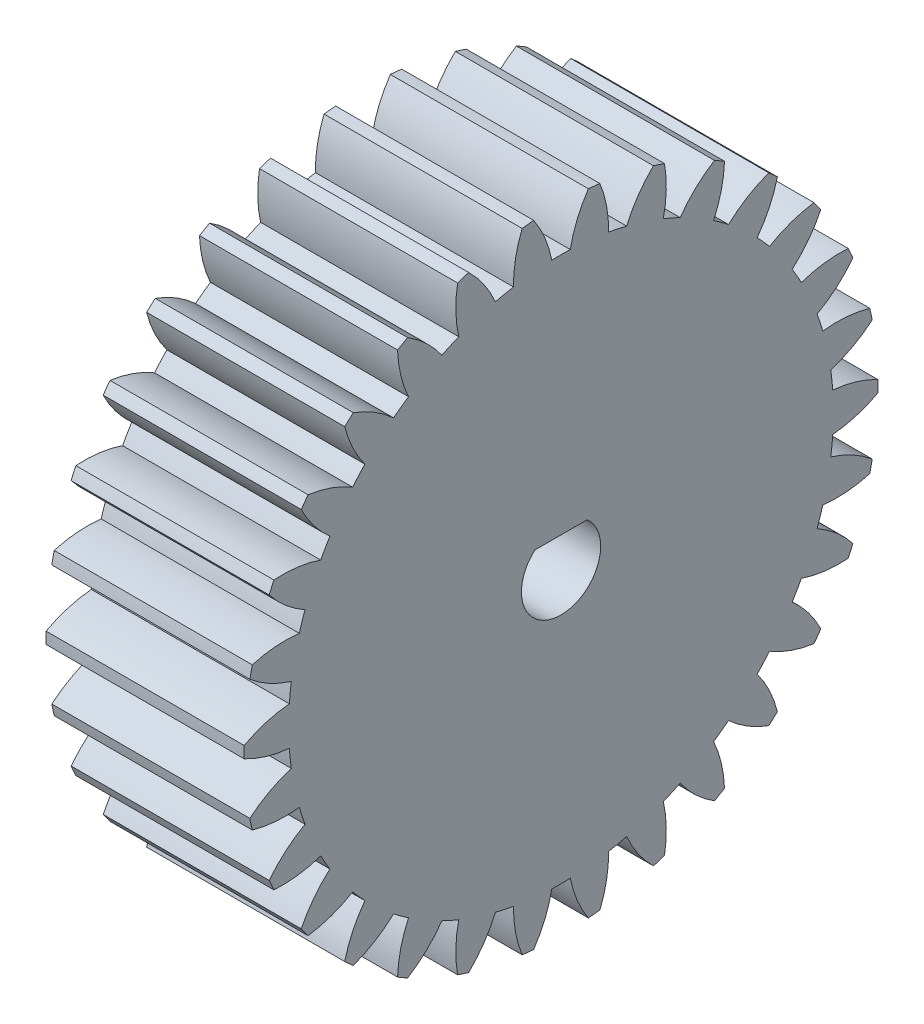
SolidWorks part; units mm, degrees
ref_plane "Plane1" through (0, 0, 0) normal (0, 0, 1) x (1, 0, 0)
ref_plane "Plane2" through (0, 0, 0) normal (0, 1, 0) x (1, 0, 0)
ref_plane "Plane3" through (0, 0, 0) normal (1, 0, 0) x (0, 0, -1)
other "Configuration Table"
sketch "HoldingSke" plane through (0, 0, 0) normal (0, 1, 0) x (1, 0, 0)
  line L0 (0, 0) -> (0.866, -0.5)
  line L1 (-15, 0) -> (100, 0) construction
  line L2 (0, 0) -> (-2.1039, 2.3779)
  line L3 (0, 0) -> (-11.863, 4.5341)
  line L4 (0, 0) -> (7.479, 4.318)
  line L5 (0, 0) -> (-46.8476, -17.4728)
  line L6 (0, 0) -> (-8.2896, -5.593)
  line L7 (-2.1039, 2.3779) -> (8.6586, 51.2059)
  line L8 (-76.2, 54.61) -> (-76.1, 54.61)
  line L9 (-71.009, 38.7566) -> (-53.1078, 45.2721)
  line L10 (-76.2, 71.12) -> (104.1128, 71.12)
  line L11 (0, 0) -> (-10, 0)
  line L12 (-76.2, 101.6) -> (-76.162, 101.6)
  line L13 (24.9733, 27.94) -> (52.9518, 28.4284)
  line L14 (24.9733, 27.94) -> (24.9743, 27.94)
  line L15 (24.9733, 27.94) -> (100.4006, 29.5858)
  line L16 (-63.627, -1) -> (-12.827, -1)
  circle A0 centre (0, 0) radius 0.4
  circle A1 centre (0, 0) radius 13.749
  circle A2 centre (0, 0) radius 37.5
  circle A3 centre (0, 0) radius 0.4
  dimension "MHD" = 27.498
  dimension "Hub_dia" = 75
  dimension "Bore" = 0.8
  dimension "MBD" = 0.8
  dimension "Num_teeth" = 30
  dimension "Pitch" = 1
  dimension "Overall_len" = 50
  dimension "Show_teeth" = 30
  dimension "Thickness" = 10
  dimension "OAL" = 50.0001
  dimension "T_dim" = 0.1
  dimension "Ap" = 20
  dimension "H" = 19.05
  dimension "Pitch_radius" = 180.3128
  dimension "Width" = 10
  dimension "Backlash" = 0.038
  dimension "Addendum_fac" = 1
  dimension "Dedendum_fac" = 1.25
  dimension "Clearance_fac" = 0.25
  dimension "Dedendum_add" = 0.001
  dimension "Module" = 1
sketch "BasProSke" plane through (0, 0, 0) normal (0, 1, 0) x (1, 0, 0)
  line L0 (-10, 0) -> (60, 0) construction
  line L1 (0, 0) -> (0, 16)
  line L2 (0, 0) -> (10, 0)
  line L3 (10, 0) -> (10, 16)
  line L4 (10, 16) -> (0, 16)
  dimension "Thickness" = 10
  dimension "Diameter" = 32
revolve "Base-Revolve" add sketch "BasProSke" angle 360 about L0
sketch "TooCutSke" plane through (0, 0, 0) normal (1, 0, 0) x (0, 0, -1)
  line L1 (0, 0) -> (0, 107) construction
  line L2 (0, 0) -> (-0.8515, 14.9758) construction
  line L3 (0, 0) -> (-3.1323, 29.8014) construction
  line L4 (-0.8515, 14.9758) -> (-1.5661, 14.9007) construction
  arc A0 (0.4664, 13.7411) -> (-0.4664, 13.7411) centre (0, 0) ccw
  arc A1 (1.3975, 15.9644) -> (-1.3975, 15.9644) centre (0, 0) ccw
  circle A2 centre (0, 0) radius 15 construction
  circle A3 centre (0, 0) radius 14.0954 construction
  arc A4 (-0.4664, 13.7411) -> (-1.3975, 15.9644) centre (-6.3534, 12.5823) ccw
  arc A5 (1.3975, 15.9644) -> (0.4664, 13.7411) centre (6.3534, 12.5823) ccw
  dimension "Root_dia" = 27.498
  dimension "Overcut_dia" = 32.0508
  dimension "Pitch_dia" = 30
  dimension "Base_dia" = 28.1908
  dimension "Flank_rad" = 6
  dimension "Half_ang" = 6
  dimension "Half_CT" = 0.7185
extrude "ToothCut" cut sketch "TooCutSke" along normal through all
fillet "Breaks" [suppressed] radius 0.02
fillet "RootFillets" [suppressed] radius 0.251
pattern_circular "TeethCuts" count 30 every 12 about axis through (-10, 0, 0) along (1, 0, 0) of "ToothCut", "RootFillets", "Breaks"
sketch "HubNeaOneSke" plane through (0, 0, 0) normal (-1, 0, 0) x (0, 0, 1)
  circle A0 centre (0, 0) radius 13.749
  dimension "Diameter" = 27.498
extrude "HubNearOne" [suppressed] add sketch "HubNeaOneSke" along normal blind 40.0001
sketch "HubNeaBotSke" plane through (0, 0, 0) normal (-1, 0, 0) x (0, 0, 1)
  circle A0 centre (0, 0) radius 13.749
  dimension "Diameter" = 27.498
extrude "HubNearBoth" [suppressed] add sketch "HubNeaBotSke" along normal blind 20
ref_plane "FarPln" through (10, 0, 0) normal (1, 0, 0) x (0, 0, -1)
sketch "HubFarSke" plane through (10, 0, 0) normal (1, 0, 0) x (0, 0, -1)
  circle A0 centre (0, 0) radius 13.749
  dimension "Diameter" = 27.498
extrude "HubFar" [suppressed] add sketch "HubFarSke" along normal blind 20
sketch "BorSke" plane through (0, 0, 0) normal (1, 0, 0) x (0, 0, -1)
  circle A0 centre (0, 0) radius 0.4
  dimension "Diameter" = 0.8
extrude "Bore" cut sketch "BorSke" along normal mid plane 100.0001
sketch "KeySke" plane through (0, 0, 0) normal (1, 0, 0) x (0, 0, -1)
  line L0 (-0.05, 0) -> (-0.05, 0.5)
  line L1 (-0.05, 0.5) -> (0.05, 0.5)
  line L2 (0.05, 0.5) -> (0.05, 0)
  line L3 (0, 0) -> (0, 34) construction
  line L4 (-0.05, 0) -> (0.05, 0)
  dimension "Offset" = 0.5
  dimension "Width" = 0.1
extrude "Keyway" [suppressed] cut sketch "KeySke" along normal mid plane 100.0001
pattern_circular "Keyway2" [suppressed] count 2 every 90 about axis through (-10, 0, 0) along (1, 0, 0)
sketch "Sketch1" plane through (10, 0, 0) normal (1, 0, 0) x (0, 0, -1)
  line L0 (-1.3229, 1.5) -> (1.3229, 1.5)
  arc A0 (-1.3229, 1.5) -> (1.3229, 1.5) centre (0, 0) ccw
  point P5 (0, -2)
  dimension "D1" = 4
  dimension "D2" = 3.5
extrude "Cut-Extrude1" cut sketch "Sketch1" against normal through all
equation "' \"Module@HoldingSke\" = 6.35"
equation "' \"Num_teeth@HoldingSke\" = 12"
equation "' \"Ap@HoldingSke\" =  20"
equation "' \"Ap@HoldingSke\" = 20"
equation "' \"Width@HoldingSke\" = 0.5 * 25.4"
equation "' \"Hub_dia@HoldingSke\"= 1 * 25.4"
equation "' \"Hub_dia@HoldingSke\" = 1 * 25.4"
equation "' \"Overall_len@HoldingSke\" = 1.0 * 25.4"
equation "' \"Bore@HoldingSke\" = 0.75 * 25.4"
equation "' \"T_dim@HoldingSke\" = 0.1 * 25.4"
equation "' \"Width@KeySke\" = 0.25 * 25.4"
equation "' \"Show_teeth@HoldingSke\" = 13"
equation "' \"Backlash@HoldingSke\" = 0.009 * 25.4"
equation "' \"Addendum_fac@HoldingSke\" = 1.0"
equation "' \"Dedendum_fac@HoldingSke\" = 1.25"
equation "' \"Dedendum_add@HoldingSke\" = 0.00005 * 25.4"
equation "' \"Clearance_fac@HoldingSke\" = 0.25"
equation "\"Pitch@HoldingSke\" = 1 / \"Module@HoldingSke\""
equation "\"Overcut_dia@TooCutSke\" = (\"Num_teeth@HoldingSke\" + 2 * \"Addendum_fac@HoldingSke\") / \"Pitch@HoldingSke\" + 0.002 * 25.4"
equation "\"Pitch_dia@TooCutSke\" = \"Num_teeth@HoldingSke\" / \"Pitch@HoldingSke\""
equation "\"Base_dia@TooCutSke\" = \"Num_teeth@HoldingSke\" / \"Pitch@HoldingSke\" * cos((\"Ap@HoldingSke\"  * 3.14159265 / 180))"
equation "\"Root_dia@TooCutSke\" = (\"Num_teeth@HoldingSke\" + 2) / \"Pitch@HoldingSke\" - 2 * (\"Addendum_fac@HoldingSke\" + \"Dedendum_fac@HoldingSke\") / \"Pitch@HoldingSke\" - \"Dedendum_add@HoldingSke\" * 2"
equation "\"Half_ang@TooCutSke\" = 180 / \"Num_teeth@HoldingSke\""
equation "\"Half_CT@TooCutSke\" = \"Num_teeth@HoldingSke\" / \"Pitch@HoldingSke\" * sin((3.14159265 / 2 / \"Num_teeth@HoldingSke\")) / 2 - 7 * \"Backlash@HoldingSke\" / 4"
equation "\"Flank_rad@TooCutSke\" = \"Num_teeth@HoldingSke\" / \"Pitch@HoldingSke\" / 5"
equation "\"Radius@RootFillets\" = \"Clearance_fac@HoldingSke\" / \"Pitch@HoldingSke\" + \"Dedendum_add@HoldingSke\""
equation "\"Break_rad@Breaks\" = 0.02 / \"Pitch@HoldingSke\""
equation "\"Thickness@HoldingSke\" = \"Width@HoldingSke\""
equation "\"OAL@HoldingSke\" = \"Thickness@HoldingSke\""
equation "\"MHD@HoldingSke\" = (\"Num_teeth@HoldingSke\" + 2) / \"Pitch@HoldingSke\" - 2 * (\"Addendum_fac@HoldingSke\" + \"Dedendum_fac@HoldingSke\")  / \"Pitch@HoldingSke\" - \"Dedendum_add@HoldingSke\" * 2"
equation "\"MBD@HoldingSke\" = (\"Num_teeth@HoldingSke\" + 2) / \"Pitch@HoldingSke\" - 2 * (\"Addendum_fac@HoldingSke\" + \"Dedendum_fac@HoldingSke\")  / \"Pitch@HoldingSke\" - \"Dedendum_add@HoldingSke\" * 2 - 0.002 * 25.4"
equation "\"MHD@HoldingSke\" = ((sgn( \"MHD@HoldingSke\" - \"Hub_dia@HoldingSke\" )-1)*( \"MHD@HoldingSke\" - \"Hub_dia@HoldingSke\" ))/-2+ \"Hub_dia@HoldingSke\""
equation "\"MBD@HoldingSke\" = ((sgn( \"MBD@HoldingSke\" - \"Bore@HoldingSke\" )-1)*( \"MBD@HoldingSke\" - \"Bore@HoldingSke\" ))/-2+ \"Bore@HoldingSke\""
equation "\"OAL@HoldingSke\" = ((sgn( \"OAL@HoldingSke\" - \"Overall_len@HoldingSke\" )+1)*( \"OAL@HoldingSke\" - \"Overall_len@HoldingSke\" ))/2 + \"Overall_len@HoldingSke\" + 0.000002 * 25.4"
equation "\"Num_teeth@TeethCuts\" = int( \"Show_teeth@HoldingSke\" ) + 1"
equation "\"Num_teeth@TeethCuts\" = ((sgn( \"Num_teeth@TeethCuts\" - \"Num_teeth@HoldingSke\" )-1)*( \"Num_teeth@TeethCuts\" - \"Num_teeth@HoldingSke\" ))/-2+ \"Num_teeth@HoldingSke\""
equation "\"Num_teeth@TeethCuts\" = ((sgn( \"Num_teeth@TeethCuts\" - 2.0)+1)*( \"Num_teeth@TeethCuts\" - 2.0))/2 +2.0"
equation "\"Angle@TeethCuts\" = 360.0 / \"Num_teeth@HoldingSke\""
equation "\"Diameter@BasProSke\" = (\"Num_teeth@HoldingSke\" + 2 * \"Addendum_fac@HoldingSke\") / \"Pitch@HoldingSke\""
equation "\"Thickness@BasProSke\"  = \"Thickness@HoldingSke\""
equation "' \"Fillet_rad@BasProSke\" =  \"Thickness@HoldingSke\" * 0.05"
equation "' \"Fillet_rad@BasProSke\" = \"Thickness@HoldingSke\" * 0.05"
equation "\"MHD@HoldingSke\" = ((sgn( \"MHD@HoldingSke\" - \"Root_dia@TooCutSke\" )-1)*( \"MHD@HoldingSke\" - \"Root_dia@TooCutSke\" ))/-2+ \"Root_dia@TooCutSke\""
equation "\"Diameter@HubNeaOneSke\" = \"MHD@HoldingSke\""
equation "\"Length@HubNearOne\" = \"OAL@HoldingSke\" - \"Thickness@BasProSke\""
equation "\"Diameter@HubNeaBotSke\" = \"MHD@HoldingSke\""
equation "\"Length@HubNearBoth\" = ( \"OAL@HoldingSke\" - \"Thickness@BasProSke\" ) / 2.0"
equation "\"Thickness@FarPln\" = \"Thickness@BasProSke\""
equation "\"Diameter@HubFarSke\" = \"MHD@HoldingSke\""
equation "\"Length@HubFar\" = ( \"OAL@HoldingSke\" - \"Thickness@BasProSke\" ) / 2.0"
equation "\"Diameter@BorSke\" = \"MBD@HoldingSke\""
equation "\"D1@Bore\" = \"OAL@HoldingSke\" * 2.0"
equation "\"D1@Keyway\" = \"OAL@HoldingSke\" * 2.0"
equation "\"Offset@KeySke\" = \"T_dim@HoldingSke\" + \"MBD@HoldingSke\" / 2.0"
